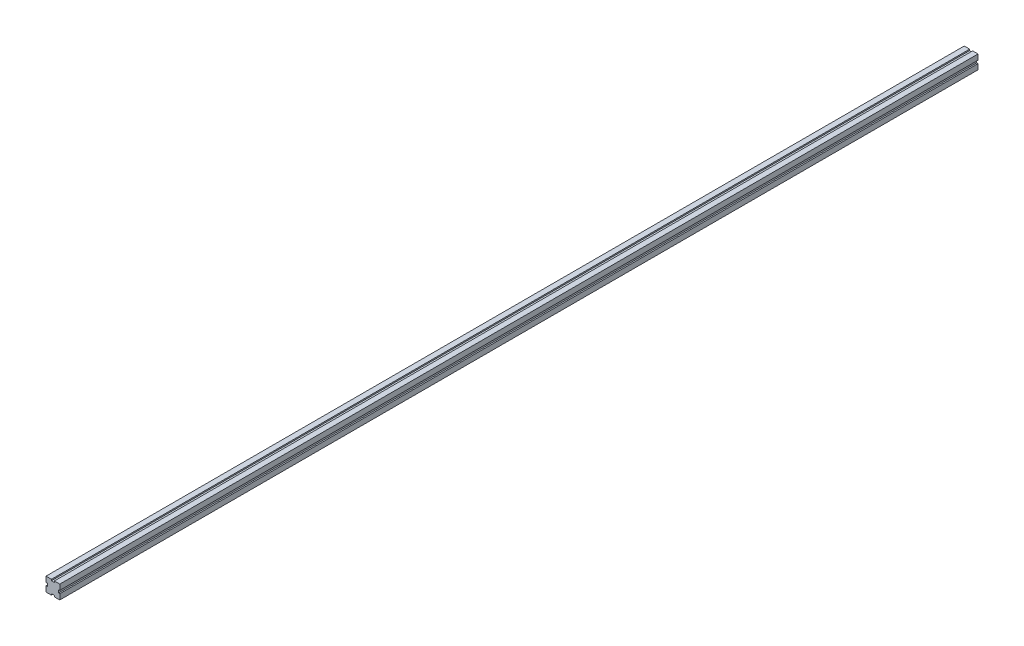
SolidWorks part; units mm, degrees
ref_plane "Front Plane" through (0, 0, 0) normal (0, 0, 1) x (1, 0, 0)
ref_plane "Top Plane" through (0, 0, 0) normal (0, 1, 0) x (1, 0, 0)
ref_plane "Right Plane" through (0, 0, 0) normal (1, 0, 0) x (0, 0, -1)
sketch "ob profile" plane through (0, 0, 0) normal (0, 0, 1) x (1, 0, 0)
  line L0 (0.8255, -2.5471) -> (0.8255, -2.7749) construction
  line L1 (0.9818, -2.97) -> (2.5094, -3.3124) construction
  line L2 (2.9, -3.8003) -> (2.9, -5.9) construction
  line L3 (2.7, -6.1) -> (2.1, -6.1) construction
  line L4 (1.6, -6.6) -> (1.6, -7) construction
  line L5 (2.1, -7.5) -> (3.9, -7.5) construction
  line L6 (4.4, -7) -> (4.4, -6.6678) construction
  line L7 (5.2536, -6.3142) -> (6.2929, -7.3536) construction
  line L8 (6.6464, -7.5) -> (7.25, -7.5) construction
  line L9 (7.5, -7.25) -> (7.5, -6.6464) construction
  line L10 (7.3536, -6.2929) -> (6.3142, -5.2536) construction
  line L11 (6.6678, -4.4) -> (7, -4.4) construction
  line L12 (7.5, -3.9) -> (7.5, -2.1) construction
  line L13 (7, -1.6) -> (6.6, -1.6) construction
  line L14 (6.1, -2.1) -> (6.1, -2.7) construction
  line L15 (5.9, -2.9) -> (3.8003, -2.9) construction
  line L16 (3.3124, -2.5094) -> (2.97, -0.9818) construction
  line L17 (2.7749, -0.8255) -> (2.5471, -0.8255) construction
  line L18 (2.3471, -0.6255) -> (2.3471, 0.6255) construction
  line L19 (2.5471, 0.8255) -> (2.7749, 0.8255) construction
  line L20 (2.97, 0.9818) -> (3.3124, 2.5094) construction
  line L21 (3.8003, 2.9) -> (5.9, 2.9) construction
  line L22 (6.1, 2.7) -> (6.1, 2.1) construction
  line L23 (6.6, 1.6) -> (7, 1.6) construction
  line L24 (7.5, 2.1) -> (7.5, 3.9) construction
  line L25 (7, 4.4) -> (6.6678, 4.4) construction
  line L26 (6.3142, 5.2536) -> (7.3536, 6.2929) construction
  line L27 (7.5, 6.6464) -> (7.5, 7.25) construction
  line L28 (7.25, 7.5) -> (6.6464, 7.5) construction
  line L29 (6.2929, 7.3536) -> (5.2536, 6.3142) construction
  line L30 (4.4, 6.6678) -> (4.4, 7) construction
  line L31 (3.9, 7.5) -> (2.1, 7.5) construction
  line L32 (1.6, 7) -> (1.6, 6.6) construction
  line L33 (2.1, 6.1) -> (2.7, 6.1) construction
  line L34 (2.9, 5.9) -> (2.9, 3.8003) construction
  line L35 (2.5094, 3.3124) -> (0.9818, 2.97) construction
  line L36 (0.8255, 2.7749) -> (0.8255, 2.5471) construction
  line L37 (0.6255, 2.3471) -> (-0.6255, 2.3471) construction
  line L38 (-0.8255, 2.5471) -> (-0.8255, 2.7749) construction
  line L39 (-0.9818, 2.97) -> (-2.5094, 3.3124) construction
  line L40 (-2.9, 3.8003) -> (-2.9, 5.9) construction
  line L41 (-2.7, 6.1) -> (-2.1, 6.1) construction
  line L42 (-1.6, 6.6) -> (-1.6, 7) construction
  line L43 (-2.1, 7.5) -> (-3.9, 7.5) construction
  line L44 (-4.4, 7) -> (-4.4, 6.6678) construction
  line L45 (-5.2536, 6.3142) -> (-6.2929, 7.3536) construction
  line L46 (-6.6464, 7.5) -> (-7.25, 7.5) construction
  line L47 (-7.5, 7.25) -> (-7.5, 6.6464) construction
  line L48 (-7.3536, 6.2929) -> (-6.3142, 5.2536) construction
  line L49 (-6.6678, 4.4) -> (-7, 4.4) construction
  line L50 (-7.5, 3.9) -> (-7.5, 2.1) construction
  line L51 (-7, 1.6) -> (-6.6, 1.6) construction
  line L52 (-6.1, 2.1) -> (-6.1, 2.7) construction
  line L53 (-5.9, 2.9) -> (-3.8003, 2.9) construction
  line L54 (-3.3124, 2.5094) -> (-2.97, 0.9818) construction
  line L55 (-2.7749, 0.8255) -> (-2.5471, 0.8255) construction
  line L56 (-2.3471, 0.6255) -> (-2.3471, -0.6255) construction
  line L57 (-2.5471, -0.8255) -> (-2.7749, -0.8255) construction
  line L58 (-2.97, -0.9818) -> (-3.3124, -2.5094) construction
  line L59 (-3.8003, -2.9) -> (-5.9, -2.9) construction
  line L60 (-6.1, -2.7) -> (-6.1, -2.1) construction
  line L61 (-6.6, -1.6) -> (-7, -1.6) construction
  line L62 (-7.5, -2.1) -> (-7.5, -3.9) construction
  line L63 (-7, -4.4) -> (-6.6678, -4.4) construction
  line L64 (-6.3142, -5.2536) -> (-7.3536, -6.2929) construction
  line L65 (-7.5, -6.6464) -> (-7.5, -7.25) construction
  line L66 (-7.25, -7.5) -> (-6.6464, -7.5) construction
  line L67 (-6.2929, -7.3536) -> (-5.2536, -6.3142) construction
  line L68 (-4.4, -6.6678) -> (-4.4, -7) construction
  line L69 (-3.9, -7.5) -> (-2.1, -7.5) construction
  line L70 (-1.6, -7) -> (-1.6, -6.6) construction
  line L71 (-2.1, -6.1) -> (-2.7, -6.1) construction
  line L72 (-2.9, -5.9) -> (-2.9, -3.8003) construction
  line L73 (-2.5094, -3.3124) -> (-0.9818, -2.97) construction
  line L74 (-0.8255, -2.7749) -> (-0.8255, -2.5471) construction
  line L75 (-0.6255, -2.3471) -> (0.6255, -2.3471) construction
  line L76 (-7.5, 7.5) -> (-1.6, 7.5)
  line L77 (-1.6, 7.5) -> (-1.6, 6.1)
  line L78 (-1.6, 6.1) -> (1.6, 6.1)
  line L79 (1.6, 6.1) -> (1.6, 7.5)
  line L80 (1.6, 7.5) -> (4.4, 7.5)
  line L81 (4.4, 7.5) -> (7.5, 7.5)
  line L82 (7.5, 7.5) -> (7.5, 1.6)
  line L83 (7.5, 1.6) -> (6.1, 1.6)
  line L84 (6.1, 1.6) -> (6.1, -1.6)
  line L85 (6.1, -1.6) -> (7.5, -1.6)
  line L86 (7.5, -1.6) -> (7.5, -7.5)
  line L87 (7.5, -7.5) -> (1.6, -7.5)
  line L88 (1.6, -7.5) -> (1.6, -6.1)
  line L89 (1.6, -6.1) -> (-1.6, -6.1)
  line L90 (-1.6, -6.1) -> (-1.6, -7.5)
  line L91 (-1.6, -7.5) -> (-7.5, -7.5)
  line L92 (-7.5, -7.5) -> (-7.5, -1.6)
  line L93 (-7.5, -1.6) -> (-6.1, -1.6)
  line L94 (-6.1, -1.6) -> (-6.1, 1.6)
  line L95 (-6.1, 1.6) -> (-7.5, 1.6)
  line L96 (-7.5, 1.6) -> (-7.5, 7.5)
  arc A0 (0.8255, -2.7749) -> (0.9818, -2.97) centre (1.0255, -2.7749) ccw construction
  arc A1 (2.9, -3.8003) -> (2.5094, -3.3124) centre (2.4, -3.8003) ccw construction
  arc A2 (2.7, -6.1) -> (2.9, -5.9) centre (2.7, -5.9) ccw construction
  arc A3 (2.1, -6.1) -> (1.6, -6.6) centre (2.1, -6.6) ccw construction
  arc A4 (1.6, -7) -> (2.1, -7.5) centre (2.1, -7) ccw construction
  arc A5 (3.9, -7.5) -> (4.4, -7) centre (3.9, -7) ccw construction
  arc A6 (5.2536, -6.3142) -> (4.4, -6.6678) centre (4.9, -6.6678) ccw construction
  arc A7 (6.2929, -7.3536) -> (6.6464, -7.5) centre (6.6464, -7) ccw construction
  arc A8 (7.25, -7.5) -> (7.5, -7.25) centre (7.25, -7.25) ccw construction
  arc A9 (7.5, -6.6464) -> (7.3536, -6.2929) centre (7, -6.6464) ccw construction
  arc A10 (6.6678, -4.4) -> (6.3142, -5.2536) centre (6.6678, -4.9) ccw construction
  arc A11 (7, -4.4) -> (7.5, -3.9) centre (7, -3.9) ccw construction
  arc A12 (7.5, -2.1) -> (7, -1.6) centre (7, -2.1) ccw construction
  arc A13 (6.6, -1.6) -> (6.1, -2.1) centre (6.6, -2.1) ccw construction
  arc A14 (5.9, -2.9) -> (6.1, -2.7) centre (5.9, -2.7) ccw construction
  arc A15 (3.3124, -2.5094) -> (3.8003, -2.9) centre (3.8003, -2.4) ccw construction
  arc A16 (2.97, -0.9818) -> (2.7749, -0.8255) centre (2.7749, -1.0255) ccw construction
  arc A17 (2.3471, -0.6255) -> (2.5471, -0.8255) centre (2.5471, -0.6255) ccw construction
  arc A18 (2.5471, 0.8255) -> (2.3471, 0.6255) centre (2.5471, 0.6255) ccw construction
  arc A19 (2.7749, 0.8255) -> (2.97, 0.9818) centre (2.7749, 1.0255) ccw construction
  arc A20 (3.8003, 2.9) -> (3.3124, 2.5094) centre (3.8003, 2.4) ccw construction
  arc A21 (6.1, 2.7) -> (5.9, 2.9) centre (5.9, 2.7) ccw construction
  arc A22 (6.1, 2.1) -> (6.6, 1.6) centre (6.6, 2.1) ccw construction
  arc A23 (7, 1.6) -> (7.5, 2.1) centre (7, 2.1) ccw construction
  arc A24 (7.5, 3.9) -> (7, 4.4) centre (7, 3.9) ccw construction
  arc A25 (6.3142, 5.2536) -> (6.6678, 4.4) centre (6.6678, 4.9) ccw construction
  arc A26 (7.3536, 6.2929) -> (7.5, 6.6464) centre (7, 6.6464) ccw construction
  arc A27 (7.5, 7.25) -> (7.25, 7.5) centre (7.25, 7.25) ccw construction
  arc A28 (6.6464, 7.5) -> (6.2929, 7.3536) centre (6.6464, 7) ccw construction
  arc A29 (4.4, 6.6678) -> (5.2536, 6.3142) centre (4.9, 6.6678) ccw construction
  arc A30 (4.4, 7) -> (3.9, 7.5) centre (3.9, 7) ccw construction
  arc A31 (2.1, 7.5) -> (1.6, 7) centre (2.1, 7) ccw construction
  arc A32 (1.6, 6.6) -> (2.1, 6.1) centre (2.1, 6.6) ccw construction
  arc A33 (2.9, 5.9) -> (2.7, 6.1) centre (2.7, 5.9) ccw construction
  arc A34 (2.5094, 3.3124) -> (2.9, 3.8003) centre (2.4, 3.8003) ccw construction
  arc A35 (0.9818, 2.97) -> (0.8255, 2.7749) centre (1.0255, 2.7749) ccw construction
  arc A36 (0.6255, 2.3471) -> (0.8255, 2.5471) centre (0.6255, 2.5471) ccw construction
  arc A37 (-0.8255, 2.5471) -> (-0.6255, 2.3471) centre (-0.6255, 2.5471) ccw construction
  arc A38 (-0.8255, 2.7749) -> (-0.9818, 2.97) centre (-1.0255, 2.7749) ccw construction
  arc A39 (-2.9, 3.8003) -> (-2.5094, 3.3124) centre (-2.4, 3.8003) ccw construction
  arc A40 (-2.7, 6.1) -> (-2.9, 5.9) centre (-2.7, 5.9) ccw construction
  arc A41 (-2.1, 6.1) -> (-1.6, 6.6) centre (-2.1, 6.6) ccw construction
  arc A42 (-1.6, 7) -> (-2.1, 7.5) centre (-2.1, 7) ccw construction
  arc A43 (-3.9, 7.5) -> (-4.4, 7) centre (-3.9, 7) ccw construction
  arc A44 (-5.2536, 6.3142) -> (-4.4, 6.6678) centre (-4.9, 6.6678) ccw construction
  arc A45 (-6.2929, 7.3536) -> (-6.6464, 7.5) centre (-6.6464, 7) ccw construction
  arc A46 (-7.25, 7.5) -> (-7.5, 7.25) centre (-7.25, 7.25) ccw construction
  arc A47 (-7.5, 6.6464) -> (-7.3536, 6.2929) centre (-7, 6.6464) ccw construction
  arc A48 (-6.6678, 4.4) -> (-6.3142, 5.2536) centre (-6.6678, 4.9) ccw construction
  arc A49 (-7, 4.4) -> (-7.5, 3.9) centre (-7, 3.9) ccw construction
  arc A50 (-7.5, 2.1) -> (-7, 1.6) centre (-7, 2.1) ccw construction
  arc A51 (-6.6, 1.6) -> (-6.1, 2.1) centre (-6.6, 2.1) ccw construction
  arc A52 (-5.9, 2.9) -> (-6.1, 2.7) centre (-5.9, 2.7) ccw construction
  arc A53 (-3.3124, 2.5094) -> (-3.8003, 2.9) centre (-3.8003, 2.4) ccw construction
  arc A54 (-2.97, 0.9818) -> (-2.7749, 0.8255) centre (-2.7749, 1.0255) ccw construction
  arc A55 (-2.3471, 0.6255) -> (-2.5471, 0.8255) centre (-2.5471, 0.6255) ccw construction
  arc A56 (-2.5471, -0.8255) -> (-2.3471, -0.6255) centre (-2.5471, -0.6255) ccw construction
  arc A57 (-2.7749, -0.8255) -> (-2.97, -0.9818) centre (-2.7749, -1.0255) ccw construction
  arc A58 (-3.8003, -2.9) -> (-3.3124, -2.5094) centre (-3.8003, -2.4) ccw construction
  arc A59 (-6.1, -2.7) -> (-5.9, -2.9) centre (-5.9, -2.7) ccw construction
  arc A60 (-6.1, -2.1) -> (-6.6, -1.6) centre (-6.6, -2.1) ccw construction
  arc A61 (-7, -1.6) -> (-7.5, -2.1) centre (-7, -2.1) ccw construction
  arc A62 (-7.5, -3.9) -> (-7, -4.4) centre (-7, -3.9) ccw construction
  arc A63 (-6.3142, -5.2536) -> (-6.6678, -4.4) centre (-6.6678, -4.9) ccw construction
  arc A64 (-7.3536, -6.2929) -> (-7.5, -6.6464) centre (-7, -6.6464) ccw construction
  arc A65 (-7.5, -7.25) -> (-7.25, -7.5) centre (-7.25, -7.25) ccw construction
  arc A66 (-6.6464, -7.5) -> (-6.2929, -7.3536) centre (-6.6464, -7) ccw construction
  arc A67 (-4.4, -6.6678) -> (-5.2536, -6.3142) centre (-4.9, -6.6678) ccw construction
  arc A68 (-4.4, -7) -> (-3.9, -7.5) centre (-3.9, -7) ccw construction
  arc A69 (-2.1, -7.5) -> (-1.6, -7) centre (-2.1, -7) ccw construction
  arc A70 (-1.6, -6.6) -> (-2.1, -6.1) centre (-2.1, -6.6) ccw construction
  arc A71 (-2.9, -5.9) -> (-2.7, -6.1) centre (-2.7, -5.9) ccw construction
  arc A72 (-2.5094, -3.3124) -> (-2.9, -3.8003) centre (-2.4, -3.8003) ccw construction
  arc A73 (-0.9818, -2.97) -> (-0.8255, -2.7749) centre (-1.0255, -2.7749) ccw construction
  arc A74 (-0.6255, -2.3471) -> (-0.8255, -2.5471) centre (-0.6255, -2.5471) ccw construction
  arc A75 (0.8255, -2.5471) -> (0.6255, -2.3471) centre (0.6255, -2.5471) ccw construction
  dimension "D1" = 15
  dimension "D2" = 3.2
extrude "Boss-Extrude1" add sketch "ob profile" along normal blind 1000
equation "\"obwidth\"=15"
equation "\"obchannel\"=3.2"
equation "\"D2@ob profile\"=\"obchannel\""
equation "\"D1@ob profile\"=\"obwidth\""
